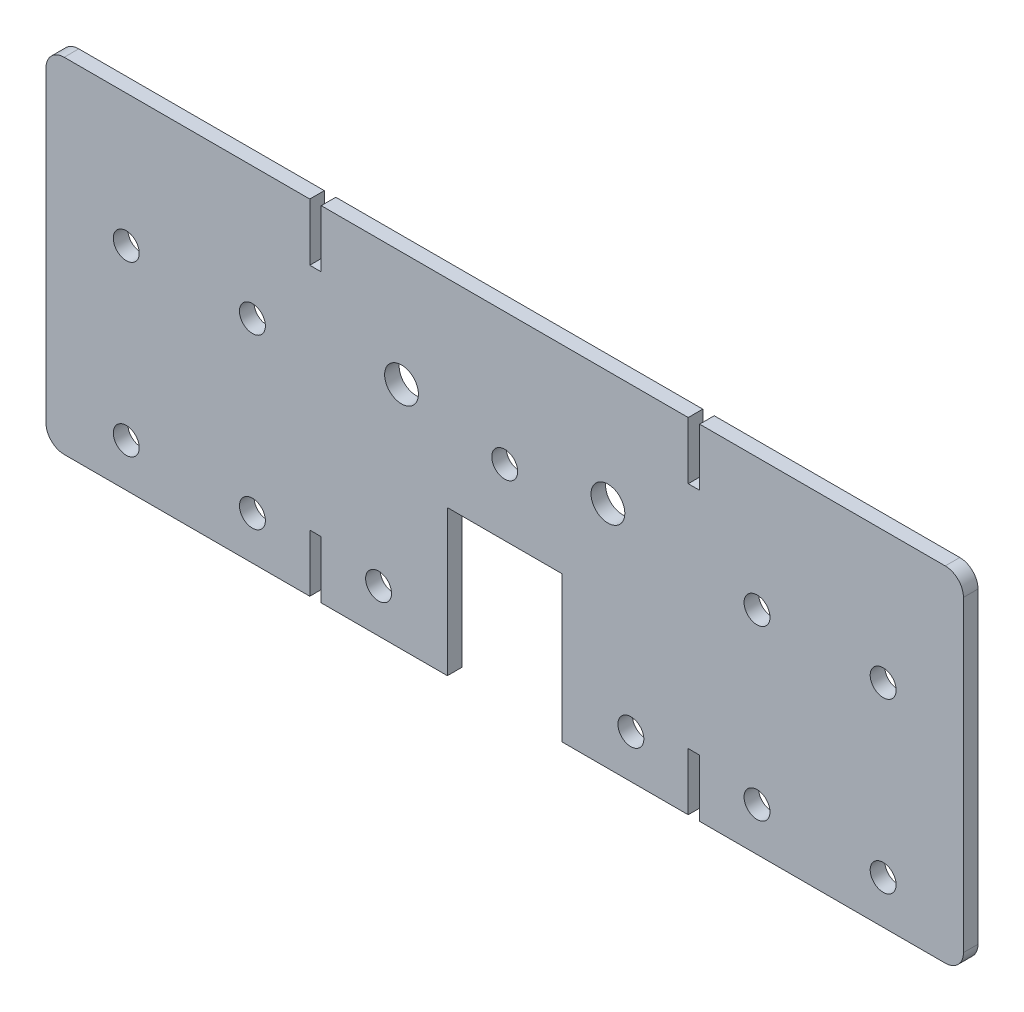
SolidWorks part; units mm, degrees
ref_plane "Front Plane" through (0, 0, 0) normal (0, 0, 1) x (1, 0, 0)
ref_plane "Top Plane" through (0, 0, 0) normal (0, 1, 0) x (1, 0, 0)
ref_plane "Right Plane" through (0, 0, 0) normal (1, 0, 0) x (0, 0, -1)
sketch "Sketch1" plane through (0, 0, 0) normal (0, 0, 1) x (1, 0, 0)
  line L0 (13, -14.7) -> (23, -14.7) construction
  line L1 (0, 0) -> (80, 0)
  line L2 (0, 0) -> (0, -30)
  line L3 (0, -30) -> (80, -30)
  line L4 (80, 0) -> (80, -30)
  line L5 (2, -2) -> (12, -2) construction
  line L6 (2, -2) -> (2, -14.7) construction
  line L7 (2, -14.7) -> (12, -14.7) construction
  line L8 (12, -2) -> (12, -14.7) construction
  line L9 (23, -2) -> (23, -14.7) construction
  line L10 (13, -2) -> (23, -2) construction
  line L11 (13, -2) -> (13, -14.7) construction
  line L12 (24, -14.7) -> (34, -14.7) construction
  line L13 (34, -2) -> (34, -14.7) construction
  line L14 (24, -2) -> (34, -2) construction
  line L15 (24, -2) -> (24, -14.7) construction
  line L16 (35, -14.7) -> (45, -14.7) construction
  line L17 (45, -2) -> (45, -14.7) construction
  line L18 (35, -2) -> (45, -2) construction
  line L19 (35, -2) -> (35, -14.7) construction
  line L20 (46, -14.7) -> (56, -14.7) construction
  line L21 (56, -2) -> (56, -14.7) construction
  line L22 (46, -2) -> (56, -2) construction
  line L23 (46, -2) -> (46, -14.7) construction
  line L24 (57, -14.7) -> (67, -14.7) construction
  line L25 (67, -2) -> (67, -14.7) construction
  line L26 (57, -2) -> (67, -2) construction
  line L27 (57, -2) -> (57, -14.7) construction
  line L28 (68, -14.7) -> (78, -14.7) construction
  line L29 (78, -2) -> (78, -14.7) construction
  line L30 (68, -2) -> (78, -2) construction
  line L31 (68, -2) -> (68, -14.7) construction
  line L32 (13, -29.4) -> (23, -29.4) construction
  line L33 (23, -16.7) -> (23, -29.4) construction
  line L34 (13, -16.7) -> (23, -16.7) construction
  line L35 (13, -16.7) -> (13, -29.4) construction
  line L36 (24, -29.4) -> (34, -29.4) construction
  line L37 (34, -16.7) -> (34, -29.4) construction
  line L38 (24, -16.7) -> (34, -16.7) construction
  line L39 (24, -16.7) -> (24, -29.4) construction
  line L40 (35, -29.4) -> (45, -29.4) construction
  line L41 (45, -16.7) -> (45, -29.4) construction
  line L42 (35, -16.7) -> (45, -16.7) construction
  line L43 (35, -16.7) -> (35, -29.4) construction
  line L44 (46, -29.4) -> (56, -29.4) construction
  line L45 (56, -16.7) -> (56, -29.4) construction
  line L46 (46, -16.7) -> (56, -16.7) construction
  line L47 (46, -16.7) -> (46, -29.4) construction
  line L48 (57, -29.4) -> (67, -29.4) construction
  line L49 (67, -16.7) -> (67, -29.4) construction
  line L50 (57, -16.7) -> (67, -16.7) construction
  line L51 (57, -16.7) -> (57, -29.4) construction
  line L52 (68, -29.4) -> (78, -29.4) construction
  line L53 (78, -16.7) -> (78, -29.4) construction
  line L54 (68, -16.7) -> (78, -16.7) construction
  line L55 (68, -16.7) -> (68, -29.4) construction
  line L56 (2, -29.4) -> (12, -29.4) construction
  line L57 (12, -16.7) -> (12, -29.4) construction
  line L58 (2, -16.7) -> (12, -16.7) construction
  line L59 (2, -16.7) -> (2, -29.4) construction
  line L60 (24, 0) -> (24, -5)
  line L61 (24, -5) -> (23, -5)
  line L62 (23, -5) -> (23, 0)
  line L63 (40, 0) -> (40, -30) construction
  line L64 (0, -15) -> (80, -15) construction
  line L65 (56, -5) -> (57, -5)
  line L66 (57, -5) -> (57, 0)
  line L67 (56, 0) -> (56, -5)
  line L68 (24, -25) -> (23, -25)
  line L69 (56, -25) -> (57, -25)
  line L70 (57, -25) -> (57, -30)
  line L71 (56, -30) -> (56, -25)
  line L72 (23, -25) -> (23, -30)
  line L73 (24, -30) -> (24, -25)
  line L75 (35, -30) -> (45, -30)
  line L76 (35, -30) -> (35, -17.3)
  line L77 (35, -17.3) -> (45, -17.3)
  line L78 (45, -30) -> (45, -17.3)
  circle A0 centre (7, -11.525) radius 1.1303
  circle A1 centre (31, -10) radius 1.4732
  circle A2 centre (49, -10) radius 1.4732
  circle A3 centre (18, -11.525) radius 1.1303
  circle A4 centre (29, -11.525) radius 1.1303 [skipped]
  circle A5 centre (40, -11.525) radius 1.1303
  circle A6 centre (51, -11.525) radius 1.1303 [skipped]
  circle A7 centre (62, -11.525) radius 1.1303
  circle A8 centre (73, -11.525) radius 1.1303
  circle A9 centre (18, -26.225) radius 1.1303
  circle A10 centre (29, -26.225) radius 1.1303
  circle A11 centre (40, -26.225) radius 1.1303
  circle A12 centre (51, -26.225) radius 1.1303
  circle A13 centre (62, -26.225) radius 1.1303
  circle A14 centre (73, -26.225) radius 1.1303
  circle A15 centre (7, -26.225) radius 1.1303
  circle A16 centre (31, -10) radius 2.3241 construction
  circle A17 centre (31, -10) radius 3.6571 construction
  point P11 (7, -14.7)
  dimension "D7" = 2.9464
  dimension "D11" = 2.2606
  dimension "D16" = 4.6482
  dimension "D1" = 3.175
  dimension "D2" = 12.7
  dimension "D3" = 10
  dimension "D4" = 2
  dimension "D5" = 2
  dimension "D6" = 18
  dimension "D8" = 80
  dimension "D9" = 31
  dimension "D10" = 10
  dimension "D14" = 2
  dimension "D15" = 2
  dimension "D17" = 30
  dimension "D18" = 5
  dimension "D19" = 10
  dimension "D20" = 12.7
  dimension "D12" = 7
  dimension "D13" = 2
extrude "Boss-Extrude1" add sketch "Sketch1" along normal blind 1.27 contours L73 L3 L71 L69 L70 L4 L1 L66 L65 L67 L60 L61 L62 L2 L72 L68 A15 A14 A13 A12 A11 A10 A9 A8 A7 A5 A3 A2 A1 A0
fillet "Fillet1" radius 1.5875 4 edges at (0, -30, 0.635) (0, 0, 0.635) (80, -30, 0.635) (80, 0, 0.635)
equation "\"D9@Sketch1\"=(\"D8@Sketch1\"-\"D6@Sketch1\")/2"
